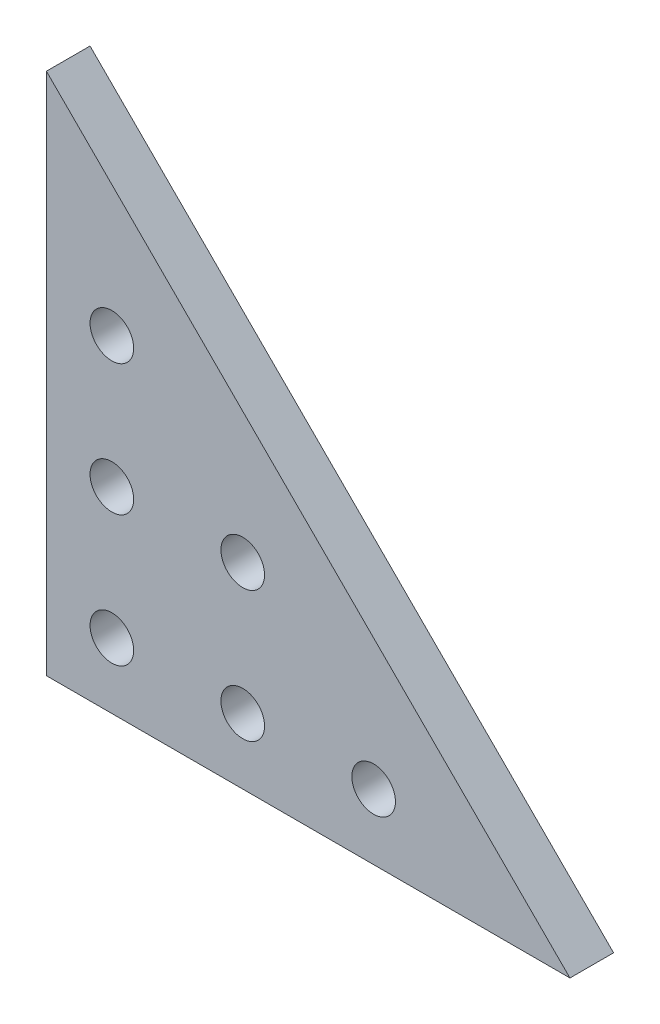
SolidWorks part; units mm, degrees
ref_plane "Alzado" through (0, 0, 0) normal (0, 0, 1) x (1, 0, 0)
ref_plane "Planta" through (0, 0, 0) normal (0, 1, 0) x (1, 0, 0)
ref_plane "Vista lateral" through (0, 0, 0) normal (1, 0, 0) x (0, 0, -1)
sketch "Model" plane through (0, 0, 0) normal (0, 0, 1) x (1, 0, 0)
  line L0 (-105.9434, 105.5565) -> (-105.9434, 69.5565)
  line L1 (-105.9434, 69.5565) -> (-69.9434, 69.5565)
  line L2 (-105.9434, 105.5565) -> (-69.9434, 69.5565)
  circle A0 centre (-101.4434, 92.0565) radius 1.5
  circle A1 centre (-101.4434, 83.0565) radius 1.5
  circle A2 centre (-92.4434, 83.0565) radius 1.5
  circle A3 centre (-101.4434, 74.0565) radius 1.5
  circle A4 centre (-92.4434, 74.0565) radius 1.5
  circle A5 centre (-83.4434, 74.0565) radius 1.5
extrude "Saliente-Extruir1" add sketch "Model" along normal blind 3
